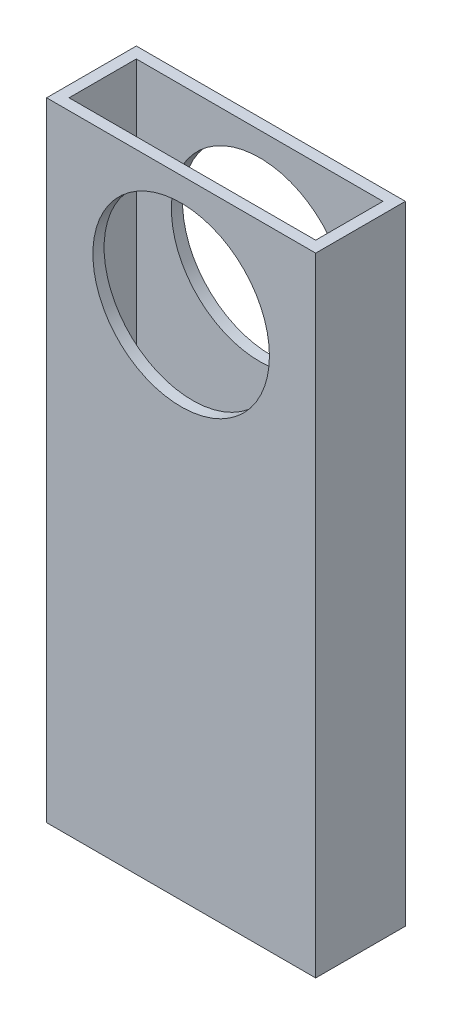
SolidWorks part; units mm, degrees
material "1060 Alloy"
ref_plane "Front Plane" through (0, 0, 0) normal (0, 0, 1) x (1, 0, 0)
ref_plane "Top Plane" through (0, 0, 0) normal (0, 1, 0) x (1, 0, 0)
ref_plane "Right Plane" through (0, 0, 0) normal (1, 0, 0) x (0, 0, -1)
sketch "Sketch1" plane through (0, 0, 0) normal (0, 1, 0) x (1, 0, 0)
  line L0 (34.925, 9.525) -> (-34.925, 9.525)
  line L1 (38.1, -12.7) -> (-38.1, -12.7)
  line L2 (38.1, -12.7) -> (38.1, 12.7)
  line L3 (38.1, 12.7) -> (-38.1, 12.7)
  line L4 (-38.1, -12.7) -> (-38.1, 12.7)
  line L5 (38.1, -12.7) -> (-38.1, 12.7) construction
  line L6 (38.1, 12.7) -> (-38.1, -12.7) construction
  line L7 (-34.925, -9.525) -> (-34.925, 9.525)
  line L8 (34.925, -9.525) -> (-34.925, -9.525)
  line L9 (34.925, -9.525) -> (34.925, 9.525)
  point P0 (0, 0)
  dimension "D1" = 76.2
  dimension "D2" = 25.4
  dimension "D3" = 3.175
extrude "Boss-Extrude1" add sketch "Sketch1" along normal blind 177.8
sketch "Sketch2" plane through (0, 0, 12.7) normal (0, 0, 1) x (1, 0, 0)
  line L0 (0, 177.8) -> (0, 146.05) construction
  line L1 (-38.1, 177.8) -> (38.1, 177.8) construction
  circle A0 centre (0, 146.05) radius 25
  dimension "D1" = 50
  dimension "D2" = 31.75
extrude "Cut-Extrude1" cut sketch "Sketch2" against normal through all
